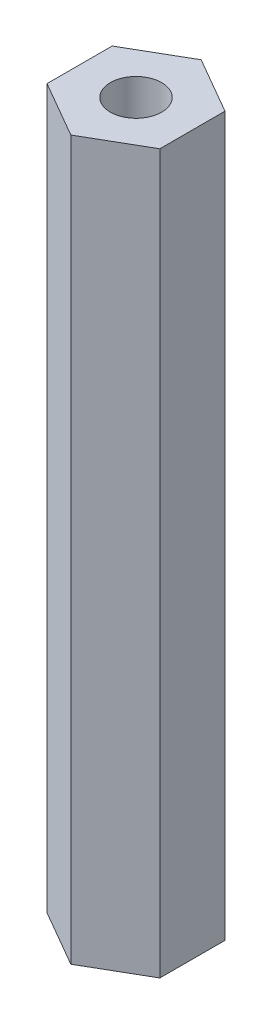
SolidWorks part; units mm, degrees
ref_plane "Front Plane" through (0, 0, 0) normal (0, 0, 1) x (1, 0, 0)
ref_plane "Top Plane" through (0, 0, 0) normal (0, 1, 0) x (1, 0, 0)
ref_plane "Right Plane" through (0, 0, 0) normal (1, 0, 0) x (0, 0, -1)
sketch "Sketch1" plane through (0, 0, 0) normal (0, 1, 0) x (1, 0, 0)
  line L1 (0, 3.1754) -> (-2.75, 1.5877)
  line L2 (-2.75, 1.5877) -> (-2.75, -1.5877)
  line L3 (-2.75, -1.5877) -> (0, -3.1754)
  line L4 (0, -3.1754) -> (2.75, -1.5877)
  line L5 (2.75, -1.5877) -> (2.75, 1.5877)
  line L6 (2.75, 1.5877) -> (0, 3.1754)
  circle A0 centre (0, 0) radius 2.75 construction
  dimension "D1" = 5.5
extrude "Boss-Extrude1" add sketch "Sketch1" along normal blind 35
hole_wizard "M3x0.5 Tapped Hole1" positions "Sketch2" profile "Sketch3" tap size "M3x0.5" standard "ANSI Metric"
sketch "Sketch2" plane through (0, 35, 0) normal (0, 1, 0) x (1, 0, 0)
  point P0 (0, 0)
sketch "Sketch3" plane through (0, 35, 0) normal (1, 0, 0) x (0, 0, 1)
  line L0 (0, 0) -> (0, 10.7511)
  line L1 (0, 10.7511) -> (1.25, 10)
  line L2 (1.25, 10) -> (1.25, 0)
  line L5 (1.25, 0) -> (0, 0)
  line L10 (0, 10.7511) -> (-1.25, 10) construction
  line L11 (0, -6.35) -> (0, 107.95) construction
  dimension "Tap Drill Dia." = 2.5
  dimension "Tap Drill Depth" = 10
  dimension "Drill Angle" = 118
hole_wizard "M3x0.5 Tapped Hole2" positions "Sketch4" profile "Sketch5" tap size "M3x0.5" standard "ANSI Metric"
sketch "Sketch4" plane through (0, 0, 0) normal (0, -1, 0) x (-1, 0, 0)
  point P0 (0, 0)
sketch "Sketch5" plane through (0, 0, 0) normal (1, 0, 0) x (0, 0, -1)
  line L0 (0, 0) -> (0, 10.7511)
  line L1 (0, 10.7511) -> (1.25, 10)
  line L2 (1.25, 10) -> (1.25, 0)
  line L5 (1.25, 0) -> (0, 0)
  line L10 (0, 10.7511) -> (-1.25, 10) construction
  line L11 (0, -6.35) -> (0, 107.95) construction
  dimension "Tap Drill Dia." = 2.5
  dimension "Tap Drill Depth" = 10
  dimension "Drill Angle" = 118
